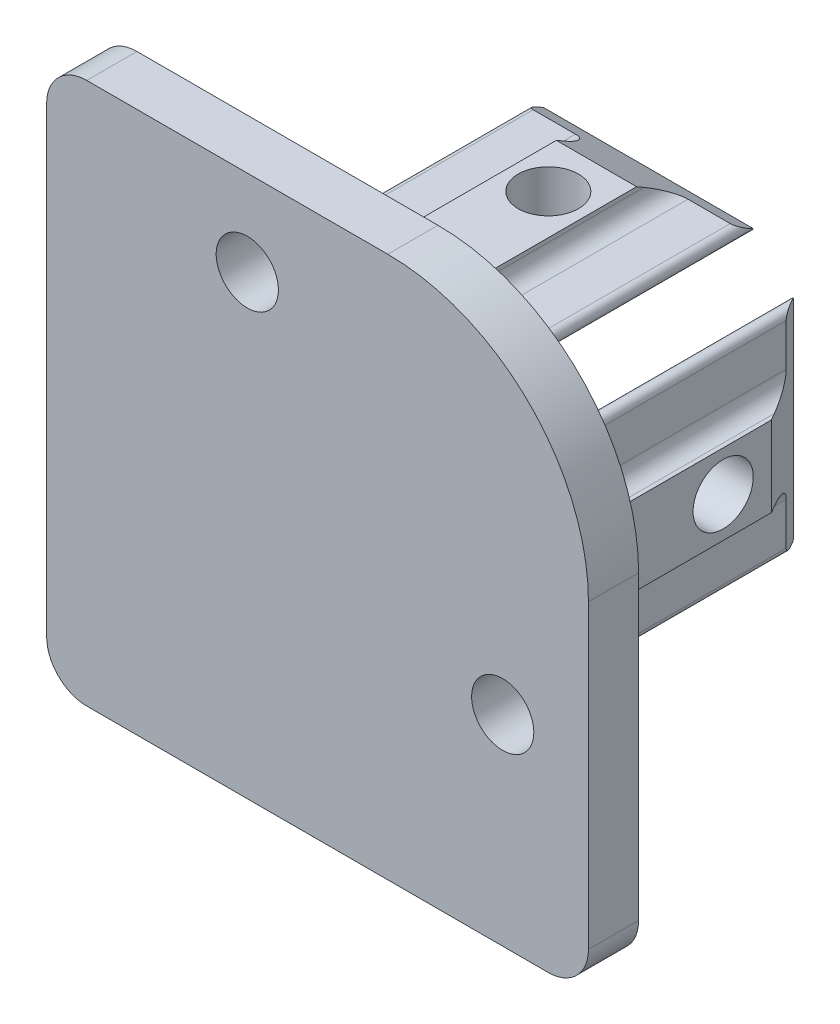
SolidWorks part; units mm, degrees
ref_plane "Front Plane" through (0, 0, 0) normal (0, 0, 1) x (1, 0, 0)
ref_plane "Top Plane" through (0, 0, 0) normal (0, 1, 0) x (1, 0, 0)
ref_plane "Right Plane" through (0, 0, 0) normal (1, 0, 0) x (0, 0, -1)
sketch "Sketch1" plane through (0, 0, 0) normal (0, 0, 1) x (1, 0, 0)
  line L72 (4.9118, -8.2) -> (2.8048, -8.2)
  line L73 (2.5, -8.5048) -> (2.5, -9.2126)
  line L74 (3.2874, -10) -> (8, -10)
  line L75 (10, -8) -> (10, -3.2874)
  line L76 (9.2126, -2.5) -> (8.5048, -2.5)
  line L77 (8.2, -2.8048) -> (8.2, -4.9118)
  line L78 (6.7691, -5.5045) -> (4.4787, -3.2141)
  line L79 (3.6, -1.0928) -> (3.6, 1.0928)
  line L80 (4.4787, 3.2141) -> (6.7691, 5.5045)
  line L81 (8.2, 4.9118) -> (8.2, 2.8048)
  line L82 (8.5048, 2.5) -> (9.2126, 2.5)
  line L83 (10, 3.2874) -> (10, 8)
  line L84 (8, 10) -> (3.2874, 10)
  line L85 (2.5, 9.2126) -> (2.5, 8.5048)
  line L86 (2.8048, 8.2) -> (4.9118, 8.2)
  line L87 (5.5045, 6.7691) -> (3.2141, 4.4787)
  line L88 (1.0928, 3.6) -> (-1.0928, 3.6)
  line L89 (-3.2141, 4.4787) -> (-5.5045, 6.7691)
  line L90 (-4.9118, 8.2) -> (-2.8048, 8.2)
  line L91 (-2.5, 8.5048) -> (-2.5, 9.2126)
  line L92 (-3.2874, 10) -> (-8, 10)
  line L93 (-10, 8) -> (-10, 3.2874)
  line L94 (-9.2126, 2.5) -> (-8.5048, 2.5)
  line L95 (-8.2, 2.8048) -> (-8.2, 4.9118)
  line L96 (-6.7691, 5.5045) -> (-4.4787, 3.2141)
  line L97 (-3.6, 1.0928) -> (-3.6, -1.0928)
  line L98 (-4.4787, -3.2141) -> (-6.7691, -5.5045)
  line L99 (-8.2, -4.9118) -> (-8.2, -2.8048)
  line L100 (-8.5048, -2.5) -> (-9.2126, -2.5)
  line L101 (-10, -3.2874) -> (-10, -8)
  line L102 (-8, -10) -> (-3.2874, -10)
  line L103 (-2.5, -9.2126) -> (-2.5, -8.5048)
  line L104 (-2.8048, -8.2) -> (-4.9118, -8.2)
  line L105 (-5.5045, -6.7691) -> (-3.2141, -4.4787)
  line L106 (-1.0928, -3.6) -> (1.0928, -3.6)
  line L107 (3.2141, -4.4787) -> (5.5045, -6.7691)
  circle A2 centre (0, 0) radius 2.15
  arc A74 (4.9118, -8.2) -> (5.5045, -6.7691) centre (4.9118, -7.3618) ccw
  arc A75 (2.8048, -8.2) -> (2.5, -8.5048) centre (2.8048, -8.5048) ccw
  arc A76 (2.5, -9.2126) -> (3.2874, -10) centre (3.2874, -9.2126) ccw
  arc A77 (8, -10) -> (10, -8) centre (8, -8) ccw
  arc A78 (10, -3.2874) -> (9.2126, -2.5) centre (9.2126, -3.2874) ccw
  arc A79 (8.5048, -2.5) -> (8.2, -2.8048) centre (8.5048, -2.8048) ccw
  arc A80 (6.7691, -5.5045) -> (8.2, -4.9118) centre (7.3618, -4.9118) ccw
  arc A81 (3.6, -1.0928) -> (4.4787, -3.2141) centre (6.6, -1.0928) ccw
  arc A82 (4.4787, 3.2141) -> (3.6, 1.0928) centre (6.6, 1.0928) ccw
  arc A83 (8.2, 4.9118) -> (6.7691, 5.5045) centre (7.3618, 4.9118) ccw
  arc A84 (8.2, 2.8048) -> (8.5048, 2.5) centre (8.5048, 2.8048) ccw
  arc A85 (9.2126, 2.5) -> (10, 3.2874) centre (9.2126, 3.2874) ccw
  arc A86 (10, 8) -> (8, 10) centre (8, 8) ccw
  arc A87 (3.2874, 10) -> (2.5, 9.2126) centre (3.2874, 9.2126) ccw
  arc A88 (2.5, 8.5048) -> (2.8048, 8.2) centre (2.8048, 8.5048) ccw
  arc A89 (5.5045, 6.7691) -> (4.9118, 8.2) centre (4.9118, 7.3618) ccw
  arc A90 (1.0928, 3.6) -> (3.2141, 4.4787) centre (1.0928, 6.6) ccw
  arc A91 (-3.2141, 4.4787) -> (-1.0928, 3.6) centre (-1.0928, 6.6) ccw
  arc A92 (-4.9118, 8.2) -> (-5.5045, 6.7691) centre (-4.9118, 7.3618) ccw
  arc A93 (-2.8048, 8.2) -> (-2.5, 8.5048) centre (-2.8048, 8.5048) ccw
  arc A94 (-2.5, 9.2126) -> (-3.2874, 10) centre (-3.2874, 9.2126) ccw
  arc A95 (-8, 10) -> (-10, 8) centre (-8, 8) ccw
  arc A96 (-10, 3.2874) -> (-9.2126, 2.5) centre (-9.2126, 3.2874) ccw
  arc A97 (-8.5048, 2.5) -> (-8.2, 2.8048) centre (-8.5048, 2.8048) ccw
  arc A98 (-6.7691, 5.5045) -> (-8.2, 4.9118) centre (-7.3618, 4.9118) ccw
  arc A99 (-3.6, 1.0928) -> (-4.4787, 3.2141) centre (-6.6, 1.0928) ccw
  arc A100 (-4.4787, -3.2141) -> (-3.6, -1.0928) centre (-6.6, -1.0928) ccw
  arc A101 (-8.2, -4.9118) -> (-6.7691, -5.5045) centre (-7.3618, -4.9118) ccw
  arc A102 (-8.2, -2.8048) -> (-8.5048, -2.5) centre (-8.5048, -2.8048) ccw
  arc A103 (-9.2126, -2.5) -> (-10, -3.2874) centre (-9.2126, -3.2874) ccw
  arc A104 (-10, -8) -> (-8, -10) centre (-8, -8) ccw
  arc A105 (-3.2874, -10) -> (-2.5, -9.2126) centre (-3.2874, -9.2126) ccw
  arc A106 (-2.5, -8.5048) -> (-2.8048, -8.2) centre (-2.8048, -8.5048) ccw
  arc A107 (-5.5045, -6.7691) -> (-4.9118, -8.2) centre (-4.9118, -7.3618) ccw
  arc A108 (-1.0928, -3.6) -> (-3.2141, -4.4787) centre (-1.0928, -6.6) ccw
  arc A109 (3.2141, -4.4787) -> (1.0928, -3.6) centre (1.0928, -6.6) ccw
sketch "Sketch2" plane through (0, 0, 0) normal (0, 0, 1) x (1, 0, 0)
  line L0 (-2.5, 9.2126) -> (2.5, 9.2126)
  line L1 (2.5, 9.2126) -> (2.5, 8.5048) construction
  line L2 (2.8048, 8.2) -> (4.9118, 8.2) construction
  line L3 (5.5045, 6.7691) -> (3.2141, 4.4787) construction
  line L4 (1.0928, 3.6) -> (-1.0928, 3.6) construction
  line L5 (-3.2141, 4.4787) -> (-5.5045, 6.7691) construction
  line L6 (-4.9118, 8.2) -> (-2.8048, 8.2) construction
  line L7 (-2.5, 8.5048) -> (-2.5, 9.2126) construction
  line L8 (2.5, 9.2126) -> (2.5, 8.5048)
  line L9 (2.8048, 8.2) -> (4.9118, 8.2)
  line L10 (5.5045, 6.7691) -> (3.2141, 4.4787)
  line L11 (1.0928, 3.6) -> (-1.0928, 3.6)
  line L12 (-3.2141, 4.4787) -> (-5.5045, 6.7691)
  line L13 (-4.9118, 8.2) -> (-2.8048, 8.2)
  line L14 (-2.5, 8.5048) -> (-2.5, 9.2126)
  line L15 (-2.8605, 4.8322) -> (-5.1509, 7.1227)
  line L16 (-4.9118, 7.7) -> (-2.8048, 7.7)
  line L17 (-2, 8.5048) -> (-2, 8.7126)
  line L18 (-2, 8.7126) -> (2, 8.7126)
  line L19 (2, 8.7126) -> (2, 8.5048)
  line L20 (2.8048, 7.7) -> (4.9118, 7.7)
  line L21 (5.1509, 7.1227) -> (2.8605, 4.8322)
  line L22 (1.0928, 4.1) -> (-1.0928, 4.1)
  arc A0 (2.5, 8.5048) -> (2.8048, 8.2) centre (2.8048, 8.5048) ccw construction
  arc A1 (5.5045, 6.7691) -> (4.9118, 8.2) centre (4.9118, 7.3618) ccw construction
  arc A2 (1.0928, 3.6) -> (3.2141, 4.4787) centre (1.0928, 6.6) ccw construction
  arc A3 (-3.2141, 4.4787) -> (-1.0928, 3.6) centre (-1.0928, 6.6) ccw construction
  arc A4 (-4.9118, 8.2) -> (-5.5045, 6.7691) centre (-4.9118, 7.3618) ccw construction
  arc A5 (-2.8048, 8.2) -> (-2.5, 8.5048) centre (-2.8048, 8.5048) ccw construction
  arc A6 (2.5, 8.5048) -> (2.8048, 8.2) centre (2.8048, 8.5048) ccw
  arc A7 (5.5045, 6.7691) -> (4.9118, 8.2) centre (4.9118, 7.3618) ccw
  arc A8 (1.0928, 3.6) -> (3.2141, 4.4787) centre (1.0928, 6.6) ccw
  arc A9 (-3.2141, 4.4787) -> (-1.0928, 3.6) centre (-1.0928, 6.6) ccw
  arc A10 (-4.9118, 8.2) -> (-5.5045, 6.7691) centre (-4.9118, 7.3618) ccw
  arc A11 (-2.8048, 8.2) -> (-2.5, 8.5048) centre (-2.8048, 8.5048) ccw
  arc A12 (-4.9118, 7.7) -> (-5.1509, 7.1227) centre (-4.9118, 7.3618) ccw
  arc A13 (-2.8048, 7.7) -> (-2, 8.5048) centre (-2.8048, 8.5048) ccw
  arc A14 (2, 8.5048) -> (2.8048, 7.7) centre (2.8048, 8.5048) ccw
  arc A15 (5.1509, 7.1227) -> (4.9118, 7.7) centre (4.9118, 7.3618) ccw
  arc A16 (1.0928, 4.1) -> (2.8605, 4.8322) centre (1.0928, 6.6) ccw
  arc A17 (-2.8605, 4.8322) -> (-1.0928, 4.1) centre (-1.0928, 6.6) ccw
  dimension "D1" = 0.5
extrude "Boss-Extrude2" add sketch "Sketch2" against normal blind 20 contours L22 A17 L15 A12 L16 A13 L17 L18 L19 A14 L20 A15 L21 A16
chamfer "Chamfer2" distance 1.5 angle 60 1 edges at (0, 8.7126, -20)
sketch "Sketch4" plane through (0, 8.7126, 0) normal (0, 1, 0) x (1, 0, 0)
  line L0 (0, 0) -> (0, 20) construction
  line L1 (-2, 20) -> (2, 20) construction
  line L2 (-3.2141, 0) -> (-1.0928, 0) construction
  circle A0 centre (0, 15) radius 1.5
  dimension "D1" = 3
  dimension "D2" = 15
extrude "Cut-Extrude1" cut sketch "Sketch4" against normal through all contours A0
sketch "Sketch5" plane through (0, 0, 0) normal (0, 0, 1) x (1, 0, 0)
  line L0 (-2, 8.7126) -> (-2, 16)
  line L1 (0, 0) -> (16, 16)
  line L3 (-2, 16) -> (16, 16)
  line L5 (10.5, 10.5) -> (2, 10.5)
  line L6 (2, 10.5) -> (2, 8.7126)
  line L7 (8, 10) -> (3.2874, 10) construction
  line L8 (2.8605, 4.8322) -> (5.1509, 7.1227)
  line L9 (4.9118, 7.7) -> (2.8048, 7.7)
  line L10 (2, 8.5048) -> (2, 8.7126)
  line L11 (2, 8.7126) -> (-2, 8.7126)
  line L12 (-2, 8.7126) -> (-2, 8.5048)
  line L13 (-2.8048, 7.7) -> (-4.9118, 7.7)
  line L14 (-5.1509, 7.1227) -> (-2.8605, 4.8322)
  line L15 (-1.0928, 4.1) -> (1.0928, 4.1)
  line L16 (2.8605, 4.8322) -> (5.1509, 7.1227)
  line L17 (4.9118, 7.7) -> (2.8048, 7.7)
  line L18 (2, 8.5048) -> (2, 8.7126)
  line L19 (2, 8.7126) -> (-2, 8.7126)
  line L20 (-2, 8.7126) -> (-2, 8.5048)
  line L21 (-2.8048, 7.7) -> (-4.9118, 7.7)
  line L22 (-5.1509, 7.1227) -> (-2.8605, 4.8322)
  line L23 (-1.0928, 4.1) -> (1.0928, 4.1)
  arc A6 (1.0928, 4.1) -> (2.8605, 4.8322) centre (1.0928, 6.6) ccw
  arc A7 (5.1509, 7.1227) -> (4.9118, 7.7) centre (4.9118, 7.3618) ccw
  arc A8 (2, 8.5048) -> (2.8048, 7.7) centre (2.8048, 8.5048) ccw
  arc A9 (-2.8048, 7.7) -> (-2, 8.5048) centre (-2.8048, 8.5048) ccw
  arc A10 (-4.9118, 7.7) -> (-5.1509, 7.1227) centre (-4.9118, 7.3618) ccw
  arc A11 (-2.8605, 4.8322) -> (-1.0928, 4.1) centre (-1.0928, 6.6) ccw
  arc A12 (1.0928, 4.1) -> (2.8605, 4.8322) centre (1.0928, 6.6) ccw
  arc A13 (5.1509, 7.1227) -> (4.9118, 7.7) centre (4.9118, 7.3618) ccw
  arc A14 (2, 8.5048) -> (2.8048, 7.7) centre (2.8048, 8.5048) ccw
  arc A15 (-2.8048, 7.7) -> (-2, 8.5048) centre (-2.8048, 8.5048) ccw
  arc A16 (-4.9118, 7.7) -> (-5.1509, 7.1227) centre (-4.9118, 7.3618) ccw
  arc A17 (-2.8605, 4.8322) -> (-1.0928, 4.1) centre (-1.0928, 6.6) ccw
  line M26 (2, 8.7126) -> (-2, 8.7126)
  dimension "D2" = 0.5
  dimension "D3" = 16
  dimension "D1" = 0
extrude "Boss-Extrude3" [suppressed] add sketch "Sketch5" against normal blind 2.5 contours L6 L5 L1 L3 L0 M26
sketch "Sketch6" plane through (0, 0, 0) normal (0, 0, 1) x (1, 0, 0)
  line L1 (-10, 17) -> (17, 17)
  line L2 (-10, 17) -> (-10, -10)
  line L3 (-10, -10) -> (17, -10)
  line L4 (17, 17) -> (17, -10)
  line L5 (-10, 8) -> (-10, 3.2874) construction
  line L7 (3.2874, -10) -> (8, -10) construction
  dimension "D1" = 17
  dimension "D2" = 17
extrude "Boss-Extrude4" add sketch "Sketch6" against normal blind 2.5
sketch "Sketch9" [suppressed] plane through (0, 0, 0) normal (1, 0, 0) x (0, 0, -1)
  line L0 (0, 0) -> (10.8044, 0) construction
pattern_circular "CirPattern1" count 4 over 360 about axis through (0, 0, 0) along (0, 0, 1) of "Boss-Extrude2", "Cut-Extrude1", "Chamfer2"
sketch "Sketch10" plane through (0, 0, 0) normal (0, 0, 1) x (1, 0, 0)
  line L0 (-10, -10) -> (17, 17) construction
  line L2 (0, 0) -> (12.7279, 0) construction
  circle A0 centre (0, 12.7279) radius 1.55
  circle A1 centre (12.7279, 0) radius 1.55
  dimension "D2" = 3.1
  dimension "D1" = 18
extrude "Cut-Extrude3" cut sketch "Sketch10" against normal through all
fillet "Fillet1" radius 10 1 edges at (17, 17, -1.25)
fillet "Fillet2" radius 2 3 edges at (-10, 17, -1.25) (-10, -10, -1.25) (17, -10, -1.25)
